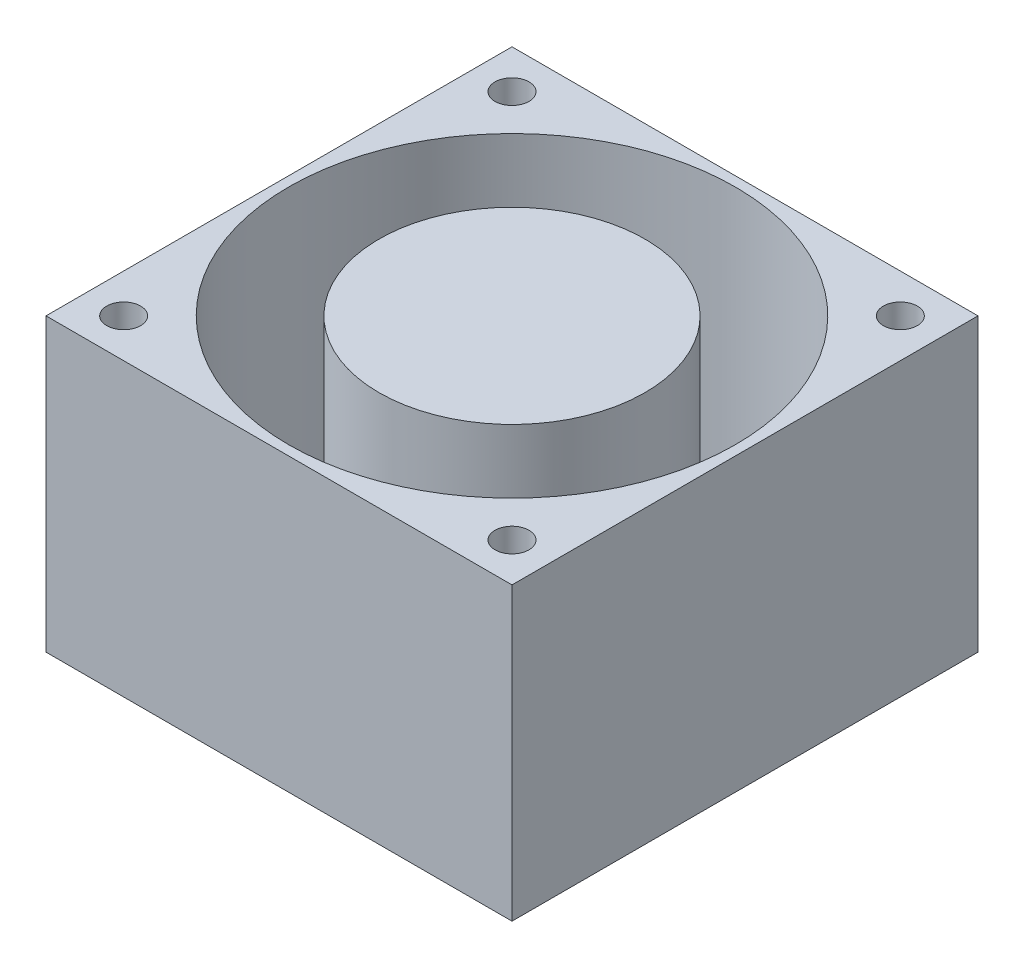
SolidWorks part; units mm, degrees
ref_plane "Front" through (0, 0, 0) normal (0, 0, 1) x (1, 0, 0)
ref_plane "Top" through (0, 0, 0) normal (0, 1, 0) x (1, 0, 0)
ref_plane "Right" through (0, 0, 0) normal (1, 0, 0) x (0, 0, -1)
sketch "Sketch1" plane through (0, 0, 0) normal (0, 1, 0) x (1, 0, 0)
  line L0 (0, 0) -> (0, -30.48)
  line L1 (0, -30.48) -> (30.48, -30.48)
  line L2 (30.48, -30.48) -> (30.48, 30.48)
  line L3 (30.48, 30.48) -> (-30.48, 30.48)
  line L4 (-30.48, 30.48) -> (-30.48, -30.48)
  line L5 (-30.48, -30.48) -> (0, -30.48)
  line L6 (0, 30.48) -> (0, 25.4)
  line L7 (0, 25.4) -> (25.4, 25.4) construction
  line L8 (25.4, 25.4) -> (25.4, -25.4) construction
  line L9 (25.4, -25.4) -> (-25.4, -25.4) construction
  line L10 (-25.4, -25.4) -> (-25.4, 25.4) construction
  line L11 (-25.4, 25.4) -> (0, 25.4) construction
  circle A0 centre (0, 0) radius 17.399
  circle A1 centre (0, 0) radius 29.21
  circle A2 centre (-25.4, 25.4) radius 2.2225
  circle A3 centre (-25.4, -25.4) radius 2.2225
  circle A4 centre (25.4, -25.4) radius 2.2225
  circle A5 centre (25.4, 25.4) radius 2.2225
extrude "Boss-Extrude1" add sketch "Sketch1" along normal blind 38.1
sketch "Sketch2" plane through (0, 0, 0) normal (0, -1, 0) x (1, 0, 0)
  line L0 (0, 0) -> (-30.48, 0) construction
  line L1 (-30.48, -30.48) -> (-30.48, 30.48) construction
  line L2 (0, 1.27) -> (-30.48, 1.27)
  line L3 (0, -1.27) -> (-30.48, -1.27)
  line L4 (0, 1.27) -> (0, -1.27)
  line L5 (-30.48, 1.27) -> (-30.48, -1.27)
  line L6 (-1.2078, -0.3925) -> (-10.6267, 28.5958)
  line L7 (1.2078, 0.3925) -> (-8.211, 29.3807)
  line L8 (-8.211, 29.3807) -> (-10.6267, 28.5958)
  line L9 (-0.7465, 1.0275) -> (23.9124, 18.9431)
  line L10 (0.7465, -1.0275) -> (25.4053, 16.8882)
  line L11 (25.4053, 16.8882) -> (23.9124, 18.9431)
  line L12 (0.7465, 1.0275) -> (25.4053, -16.8882)
  line L13 (-0.7465, -1.0275) -> (23.9124, -18.9431)
  line L14 (23.9124, -18.9431) -> (25.4053, -16.8882)
  line L15 (1.2078, -0.3925) -> (-8.211, -29.3807)
  line L16 (-1.2078, 0.3925) -> (-10.6267, -28.5958)
  line L17 (-10.6267, -28.5958) -> (-8.211, -29.3807)
  point P27 (0, 0)
  circle M6 centre (0, 0) radius 17.399
  dimension "D1" = 1.27
  dimension "D2" = 1.27
  dimension "D3" = 5
extrude "Boss-Extrude2" add sketch "Sketch2" against normal blind 2.54 contours L7 L8 L6 M6 | L10 L11 L9 M6 | L13 L14 L12 M6 | L16 L17 L15 M6 | L0 L5 L3 M6 | L0 L2 L5 M6
